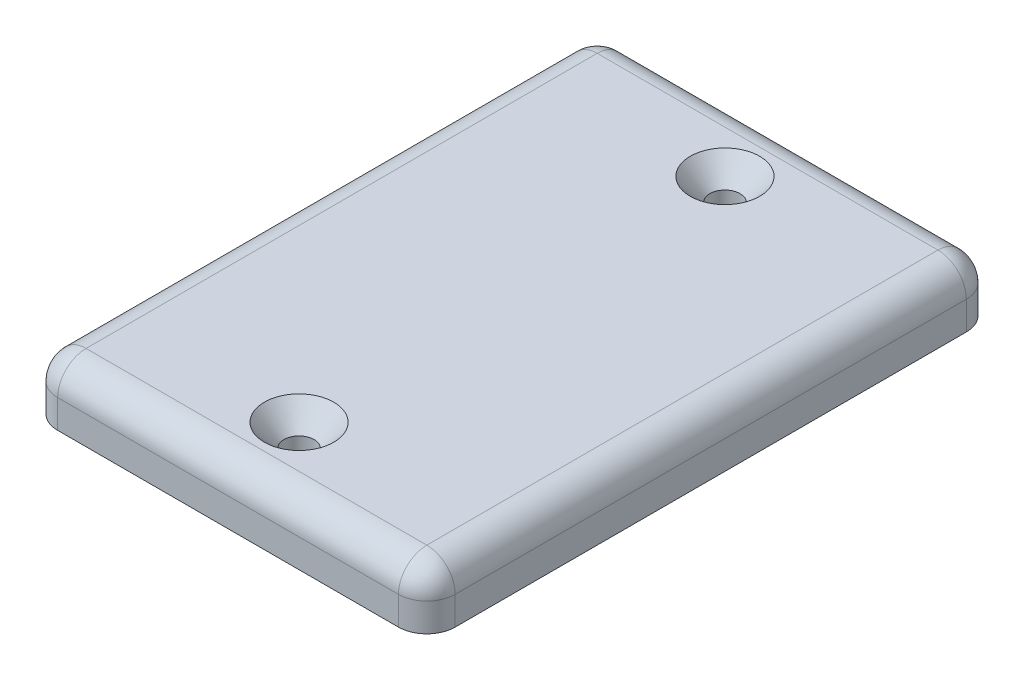
SolidWorks part; units mm, degrees
material "PE High Density"
ref_plane "Front Plane" through (0, 0, 0) normal (0, 0, 1) x (1, 0, 0)
ref_plane "Top Plane" through (0, 0, 0) normal (0, 1, 0) x (1, 0, 0)
ref_plane "Right Plane" through (0, 0, 0) normal (1, 0, 0) x (0, 0, -1)
sketch "Sketch1" plane through (0, 0, 0) normal (0, 1, 0) x (1, 0, 0)
  line L1 (0, 0) -> (88.9, 0)
  line L2 (0, 0) -> (0, 127)
  line L3 (0, 127) -> (88.9, 127)
  line L4 (88.9, 0) -> (88.9, 127)
  dimension "D1" = 88.9
  dimension "D2" = 127
extrude "Boss-Extrude1" add sketch "Sketch1" along normal blind 12.7
hole_wizard "CSK for 1/4 Flat Head Machine Screw1" positions "Sketch2" profile "Sketch3" countersink size "1/4" standard "ANSI Inch" end condition through all
sketch "Sketch2" plane through (0, 12.7, 0) normal (0, 1, 0) x (-1, 0, 0)
  line L0 (-44.45, -127) -> (-44.45, -111.125) construction
  line L1 (-88.9, -127) -> (0, -127) construction
  line L3 (-44.45, 0) -> (-44.45, -15.875) construction
  line L4 (0, 0) -> (-88.9, 0) construction
  point P2 (-44.45, -111.125)
  point P8 (-44.45, -15.875)
  dimension "D1" = 15.875
sketch "Sketch3" plane through (44.45, 12.7, -15.875) normal (1, 0, 0) x (0, 0, 1)
  line L0 (0, 0) -> (0, 12.7)
  line L1 (0, 12.7) -> (3.3782, 12.7)
  line L2 (3.3782, 12.7) -> (3.3782, 5.0449)
  line L3 (3.3782, 5.0449) -> (7.7637, 0)
  line L5 (7.7637, 0) -> (0, 0)
  line L6 (-3.3782, 5.0449) -> (-7.7637, 0) construction
  line L11 (0, -6.35) -> (0, 107.95) construction
  dimension "Thru Hole Dia." = 6.7564
  dimension "Thru Hole Depth" = 12.7
  dimension "Near C'Sink Dia." = 15.5274
  dimension "Near C'Sink Angle" = 82
fillet "Fillet1" radius 6.35 4 edges at (0, 6.35, 0) (0, 6.35, -127) (88.9, 6.35, 0) (88.9, 6.35, -127)
fillet "Fillet2" radius 6.35 8 edges at (87.0401, 12.7, -125.1401) (88.9, 12.7, -63.5) (87.0401, 12.7, -1.8599) (44.45, 12.7, 0) (1.8599, 12.7, -1.8599) (0, 12.7, -63.5) (1.8599, 12.7, -125.1401) (44.45, 12.7, -127)
